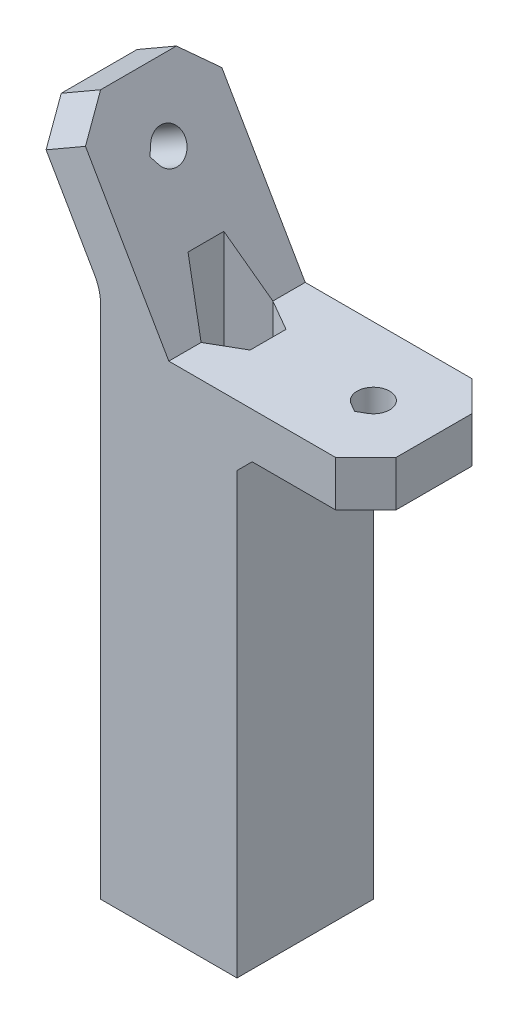
SolidWorks part; units mm, degrees
ref_plane "Front Plane" through (0, 0, 0) normal (0, 0, 1) x (1, 0, 0)
ref_plane "Top Plane" through (0, 0, 0) normal (0, 1, 0) x (1, 0, 0)
ref_plane "Right Plane" through (0, 0, 0) normal (1, 0, 0) x (0, 0, -1)
sketch "Sketch1" plane through (0, 0, 0) normal (0, 0, 1) x (1, 0, 0)
  line L0 (-14.7321, 25.5167) -> (0, 0)
  line L1 (0, 0) -> (29.4641, 0)
  line L2 (-14.7321, 25.5167) -> (-9.5359, 28.5167)
  line L3 (-9.5359, 28.5167) -> (3.4641, 6)
  line L4 (3.4641, 6) -> (29.4641, 6)
  line L5 (29.4641, 6) -> (29.4641, 0)
  dimension "D1" = 120
  dimension "D2" = 6
  dimension "D3" = 26
extrude "Boss-Extrude1" add sketch "Sketch1" along normal mid plane 18
sketch "Sketch2" plane through (0, 6, 0) normal (0, 1, 0) x (1, 0, 0)
  line L0 (3.4641, 0) -> (21.4641, 0) construction
  line L1 (3.4641, -9) -> (3.4641, 9) construction
  circle A0 centre (21.4641, 0) radius 2.15
  dimension "D1" = 4.3
  dimension "D2" = 18
extrude "Cut-Extrude1" cut sketch "Sketch2" against normal through all
sketch "Sketch3" plane through (5.1962, 3, 0) normal (0.866, 0.5, 0) x (0, 0, -1)
  line L0 (0, 3.4641) -> (0, 21.4641) construction
  line L1 (-9, 3.4641) -> (9, 3.4641) construction
  circle A0 centre (0, 21.4641) radius 2.15
  dimension "D1" = 4.3
  dimension "D2" = 18
extrude "Cut-Extrude2" cut sketch "Sketch3" against normal through all
sketch "Sketch4" plane through (0, 0, -9) normal (0, 0, -1) x (-1, 0, 0)
  line L0 (0, 0) -> (-12.4641, 0)
  line L1 (0, 0) -> (-29.4641, 0) construction
  line L2 (-12.4641, 0) -> (-12.4641, -60)
  line L3 (-12.4641, -60) -> (5.5359, -60)
  line L4 (5.5359, -60) -> (5.5359, 9.5885)
  line L5 (14.7321, 25.5167) -> (0, 0) construction
  line L6 (5.5359, 9.5885) -> (0, 0)
  line L7 (0, 0) -> (0, -12) construction
  line L8 (-3.4641, 6) -> (-3.4641, -60) construction
  dimension "D1" = 18
  dimension "D2" = 60
extrude "Boss-Extrude2" add sketch "Sketch4" against normal up to surface (18 mm away) up to face at (6.3541, 11.0056, 9)
chamfer "Chamfer1" distance 4 angle 45 4 edges at (-12.134, 27.0167, -9) (-12.134, 27.0167, 9) (29.4641, 3, -9) (29.4641, 3, 9)
chamfer "Chamfer2" distance 2 angle 45 1 edges at (12.4641, 0, 0)
fillet "Fillet1" radius 6 1 edges at (-5.5359, 9.5885, 0)
sketch "Sketch5" plane through (5.1962, 3, 0) normal (0.866, 0.5, 0) x (0, 0, -1)
  line L0 (-1.862, 22.5391) -> (-2.4826, 21.4641)
  line L1 (-2.4826, 21.4641) -> (-1.862, 20.3891)
  line L2 (-1.862, 20.3891) -> (-1.862, 22.5391)
  circle A0 centre (0, 21.4641) radius 2.15 construction
  circle A1 centre (0, 21.4641) radius 2.15 construction
  dimension "D1" = 120
extrude "Cut-Extrude3" cut sketch "Sketch5" against normal through all
sketch "Sketch6" plane through (0, 6, 0) normal (0, 1, 0) x (1, 0, 0)
  line L0 (22.5391, -1.862) -> (21.4641, -2.4826)
  line L1 (21.4641, -2.4826) -> (20.3891, -1.862)
  line L2 (20.3891, -1.862) -> (22.5391, -1.862)
  circle A0 centre (21.4641, 0) radius 2.15 construction
  circle A1 centre (21.4641, 0) radius 2.15 construction
  dimension "D1" = 120
extrude "Cut-Extrude4" cut sketch "Sketch6" against normal through all
sketch "Sketch7" plane through (0, -60, 0) normal (0, -1, 0) x (1, 0, 0)
  line L0 (12.4641, 9) -> (-5.5359, -9) construction
  circle A0 centre (3.4641, 0) radius 2.65
  dimension "D1" = 5.3
extrude "Cut-Extrude5" cut sketch "Sketch7" against normal through all
sketch "Sketch8" plane through (0, -60, 0) normal (0, -1, 0) x (1, 0, 0)
  line L1 (3.4641, 4.7343) -> (-0.6359, 2.3671)
  line L2 (-0.6359, 2.3671) -> (-0.6359, -2.3671)
  line L3 (-0.6359, -2.3671) -> (3.4641, -4.7343)
  line L4 (3.4641, -4.7343) -> (7.5641, -2.3671)
  line L5 (7.5641, -2.3671) -> (7.5641, 2.3671)
  line L6 (7.5641, 2.3671) -> (3.4641, 4.7343)
  circle A0 centre (3.4641, 0) radius 4.1 construction
  dimension "D1" = 8.2
extrude "Cut-Extrude6" cut sketch "Sketch8" against normal through all from offset 6 offset against normal yes
sketch "Sketch10" plane through (0, -60, 0) normal (0, -1, 0) x (1, 0, 0)
  line L0 (2.1391, 2.295) -> (3.4641, 3.06)
  line L1 (3.4641, 3.06) -> (4.7891, 2.295)
  line L2 (4.7891, 2.295) -> (2.1391, 2.295)
  circle A0 centre (3.4641, 0) radius 2.65 construction
  circle A1 centre (3.4641, 0) radius 2.65 construction
  dimension "D1" = 120
extrude "Cut-Extrude7" cut sketch "Sketch10" against normal through all
